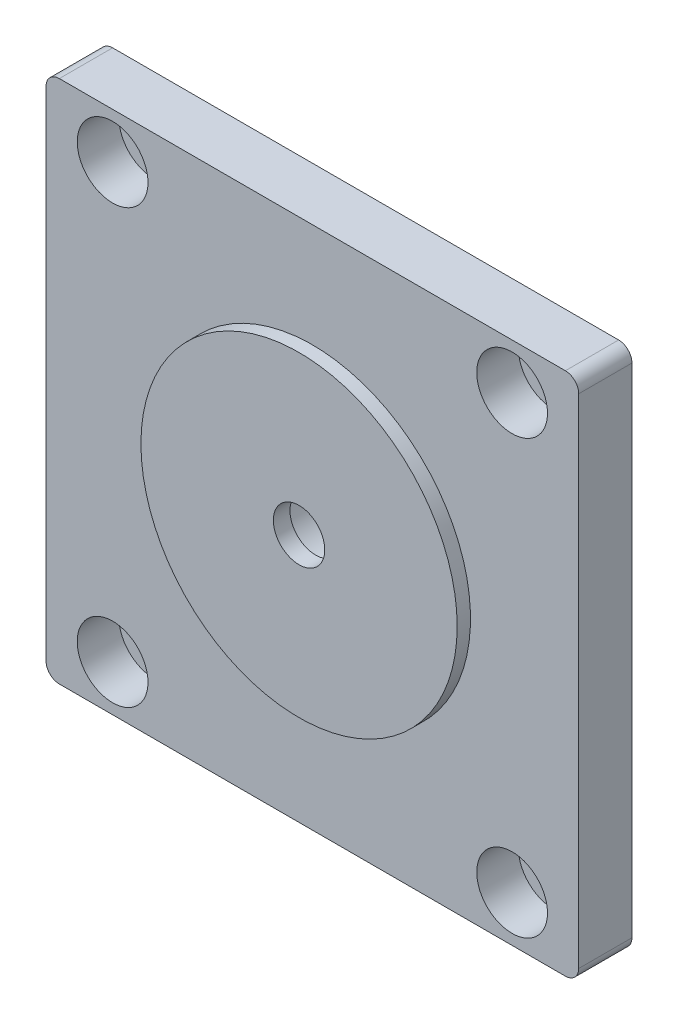
SolidWorks part; units mm, degrees
ref_plane "Front Plane" through (0, 0, 0) normal (0, 0, 1) x (1, 0, 0)
ref_plane "Top Plane" through (0, 0, 0) normal (0, 1, 0) x (1, 0, 0)
ref_plane "Right Plane" through (0, 0, 0) normal (1, 0, 0) x (0, 0, -1)
sketch "Sketch1" plane through (0, 0, 0) normal (0, 0, 1) x (1, 0, 0)
  line L1 (0, 0) -> (101.6, 0)
  line L2 (0, 0) -> (0, 100.0125)
  line L3 (0, 100.0125) -> (101.6, 100.0125)
  line L4 (101.6, 0) -> (101.6, 100.0125)
  dimension "D1" = 101.6
  dimension "D2" = 100.0125
extrude "Boss-Extrude1" add sketch "Sketch1" along normal blind 10.16
hole_wizard "CBORE for 5/16 Socket Head Cap Screw1" positions "Sketch2" profile "Sketch3" counterbore size "5/16" standard "ANSI Inch" end condition through all
sketch "Sketch2" plane through (0, 0, 10.16) normal (0, 0, 1) x (1, 0, 0)
  line L0 (0, 100.0125) -> (101.6, 0) construction
  line L3 (12.7, 8.7313) -> (88.9, 8.7313) construction
  line L4 (12.7, 8.7313) -> (12.7, 91.2813) construction
  line L5 (12.7, 91.2813) -> (88.9, 91.2813) construction
  line L6 (88.9, 8.7313) -> (88.9, 91.2813) construction
  line L7 (12.7, 8.7313) -> (88.9, 91.2813) construction
  line L8 (12.7, 91.2813) -> (88.9, 8.7313) construction
  line L9 (0, 100.0125) -> (0, 0) construction
  line L10 (0, 0) -> (101.6, 0) construction
  point P8 (88.9, 91.2813)
  point P41 (12.7, 8.7313)
  point P42 (12.7, 91.2813)
  point P43 (88.9, 8.7313)
  point P54 (0, 0)
  dimension "D1" = 76.2
  dimension "D2" = 82.55
  dimension "D3" = 12.7
  dimension "D4" = 8.7313
sketch "Sketch3" plane through (88.9, 8.7313, 10.16) normal (1, 0, 0) x (0, -1, 0)
  line L0 (0, 0) -> (0, 10.16)
  line L1 (0, 10.16) -> (4.1021, 10.16)
  line L3 (4.1021, 10.16) -> (4.1021, 7.9375)
  line L4 (4.1021, 7.9375) -> (6.7475, 7.9375)
  line L5 (6.7475, 7.9375) -> (6.7475, 0)
  line L7 (6.7475, 0) -> (0, 0)
  line L11 (0, -6.35) -> (0, 107.95) construction
  dimension "Thru Hole Dia." = 8.2042
  dimension "Thru Hole Depth" = 10.16
  dimension "C'Bore Dia." = 13.495
  dimension "C'Bore Depth" = 7.9375
sketch "Sketch4" plane through (0, 0, 10.16) normal (0, 0, 1) x (1, 0, 0)
  line L0 (0, 100.0125) -> (101.6, 0) construction
  circle A0 centre (50.8, 50.0062) radius 30.1625
  dimension "D1" = 60.325
extrude "Boss-Extrude2" add sketch "Sketch4" along normal blind 2.54
hole_wizard "CBORE for 3/8 Socket Head Cap Screw1" positions "Sketch7" profile "Sketch8" counterbore size "3/8" standard "ANSI Inch" end condition through all
sketch "Sketch7" plane through (0, 0, 0) normal (0, 0, -1) x (-1, 0, 0)
  line L0 (-101.6, 100.0125) -> (0, 0) construction
  point P6 (-50.8, 50.0062)
sketch "Sketch8" plane through (50.8, 50.0062, 0) normal (1, 0, 0) x (0, 1, 0)
  line L0 (0, 0) -> (0, 12.7)
  line L1 (0, 12.7) -> (4.9022, 12.7)
  line L3 (4.9022, 12.7) -> (4.9022, 9.525)
  line L4 (4.9022, 9.525) -> (7.9375, 9.525)
  line L5 (7.9375, 9.525) -> (7.9375, 0)
  line L7 (7.9375, 0) -> (0, 0)
  line L11 (0, -6.35) -> (0, 107.95) construction
  dimension "Thru Hole Dia." = 9.8044
  dimension "Thru Hole Depth" = 12.7
  dimension "C'Bore Dia." = 15.875
  dimension "C'Bore Depth" = 9.525
fillet "Fillet1" radius 2.54 4 edges at (101.6, 0, 5.08) (0, 100.0125, 5.08) (0, 0, 5.08) (101.6, 100.0125, 5.08)
